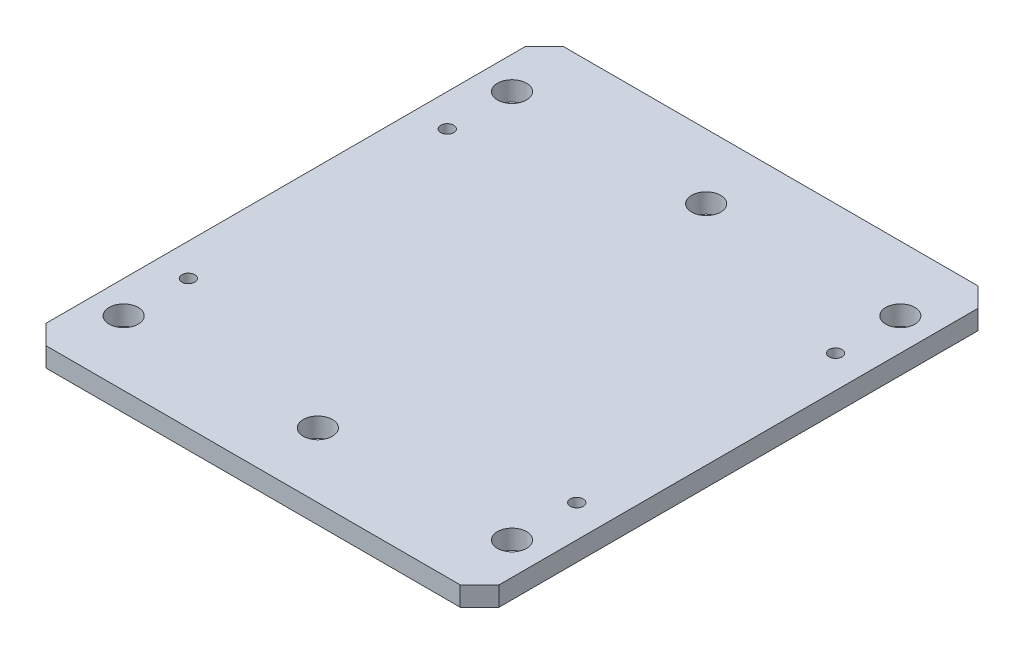
SolidWorks part; units mm, degrees
ref_plane "Plan de face" through (0, 0, 0) normal (0, 0, 1) x (1, 0, 0)
ref_plane "Plan de dessus" through (0, 0, 0) normal (0, 1, 0) x (1, 0, 0)
ref_plane "Plan de droite" through (0, 0, 0) normal (1, 0, 0) x (0, 0, -1)
sketch "Esquisse1" plane through (0, 0, 0) normal (0, 0, 1) x (1, 0, 0)
  line L1 (0, 0) -> (70, 0)
  line L2 (0, 0) -> (0, 12)
  line L3 (0, 12) -> (70, 12)
  line L4 (70, 0) -> (70, 12)
  dimension "D1" = 12
  dimension "D2" = 70
extrude "Boss.-Extru.1" add sketch "Esquisse1" along normal blind 80
sketch "Esquisse2" plane through (0, 0, 80) normal (0, 0, 1) x (1, 0, 0)
  line L0 (35, 0) -> (35, 12) construction
  line L1 (0, 0) -> (70, 0) construction
  line L2 (70, 12) -> (0, 12) construction
  line L3 (58.5, 12) -> (58.5, 6)
  line L4 (23.5, 12) -> (11.5, 12)
  line L5 (23.5, 12) -> (23.5, 6)
  line L6 (23.5, 6) -> (11.5, 6)
  line L7 (11.5, 12) -> (11.5, 6)
  line L8 (46.5, 6) -> (58.5, 6)
  line L9 (46.5, 12) -> (46.5, 6)
  line L10 (46.5, 12) -> (58.5, 12)
  dimension "D1" = 12
  dimension "D2" = 6
  dimension "D3" = 23
extrude "Enlèv. mat.-Extru.1" cut sketch "Esquisse2" against normal through all
sketch "Esquisse4" plane through (0, 12, 0) normal (0, 1, 0) x (1, 0, 0)
  line L0 (0, -10) -> (70, -10) construction
  line L1 (0, -80) -> (0, 0) construction
  line L3 (0, -40) -> (70, -40) construction
  line L4 (70, -80) -> (70, 0) construction
  line L5 (46.5, 0) -> (23.5, 0) construction
  line L6 (0, -70) -> (70, -70) construction
  line L8 (35, -10) -> (35, -70) construction
  circle A0 centre (5, -10) radius 2.25
  circle A1 centre (65, -70) radius 2.25
  circle A2 centre (65, -10) radius 2.25
  circle A3 centre (5, -70) radius 2.25
  circle A4 centre (35, -10) radius 2.25
  circle A5 centre (35, -70) radius 2.25
  dimension "D1" = 4.5
  dimension "D2" = 30
  dimension "D4" = 10
extrude "Enlèv. mat.-Extru.3" cut sketch "Esquisse4" against normal through all
sketch "Esquisse5" plane through (0, 12, 0) normal (0, 1, 0) x (1, 0, 0)
  line L0 (23.5, 0) -> (23.5, -80) construction
  line L1 (11.5, -80) -> (23.5, -80)
  line L2 (11.5, -80) -> (11.5, -70)
  line L3 (11.5, -70) -> (23.5, -70)
  line L4 (23.5, -80) -> (23.5, -70)
  line L5 (35, -80) -> (35, 0) construction
  line L6 (46.5, -80) -> (23.5, -80) construction
  line L7 (46.5, 0) -> (23.5, 0) construction
  line L8 (70, -40) -> (0, -40) construction
  line L9 (70, -80) -> (70, 0) construction
  line L10 (0, -80) -> (0, 0) construction
  line L11 (46.5, -80) -> (46.5, -70)
  line L12 (58.5, -70) -> (46.5, -70)
  line L13 (58.5, -80) -> (58.5, -70)
  line L14 (58.5, -80) -> (46.5, -80)
  line L15 (58.5, 0) -> (46.5, 0)
  line L16 (58.5, 0) -> (58.5, -10)
  line L17 (58.5, -10) -> (46.5, -10)
  line L18 (46.5, 0) -> (46.5, -10)
  line L19 (23.5, 0) -> (23.5, -10)
  line L20 (11.5, -10) -> (23.5, -10)
  line L21 (11.5, 0) -> (11.5, -10)
  line L22 (11.5, 0) -> (23.5, 0)
  dimension "D1" = 10
extrude "Boss.-Extru.2" add sketch "Esquisse5" against normal up to vertex (6 mm away) up to point (46.5, 6, 0)
chamfer "Chanfrein1" distance 3 angle 45 4 edges at (0, 6, 0) (70, 6, 0) (70, 6, 80) (0, 6, 80)
sketch "Esquisse6" plane through (0, 12, 0) normal (0, 1, 0) x (1, 0, 0)
  line L0 (35, -80) -> (35, 0) construction
  line L1 (67, -80) -> (3, -80) construction
  line L2 (67, 0) -> (3, 0) construction
  line L3 (5, -20) -> (35, -20) construction
  line L4 (0, -40) -> (35, -40) construction
  line L5 (0, -77) -> (0, -3) construction
  line L6 (5, -20) -> (5, -40) construction
  line L7 (65, -20) -> (65, -40) construction
  circle A0 centre (5, -20) radius 1
  circle A1 centre (5, -60) radius 1
  circle A2 centre (65, -60) radius 1
  circle A3 centre (65, -20) radius 1
  dimension "D2" = 2
  dimension "D1" = 30
  dimension "D3" = 20
extrude "Enlèv. mat.-Extru.4" cut sketch "Esquisse6" against normal up to vertex (12 mm away) up to point (70, 0, 3)
sketch "Esquisse8" plane through (0, 0, 80) normal (0, 0, 1) x (1, 0, 0)
  line L0 (70, 12) -> (70, 0) construction
  line L1 (0, 3) -> (70, 3)
  line L2 (0, 3) -> (0, 12)
  line L3 (0, 12) -> (70, 12)
  line L4 (70, 3) -> (70, 12)
  line L5 (0, 0) -> (0, 12) construction
  line L6 (3, 0) -> (67, 0) construction
  dimension "D1" = 3
extrude "Enlèv. mat.-Extru.8" cut sketch "Esquisse8" against normal up to vertex (80 mm away)
